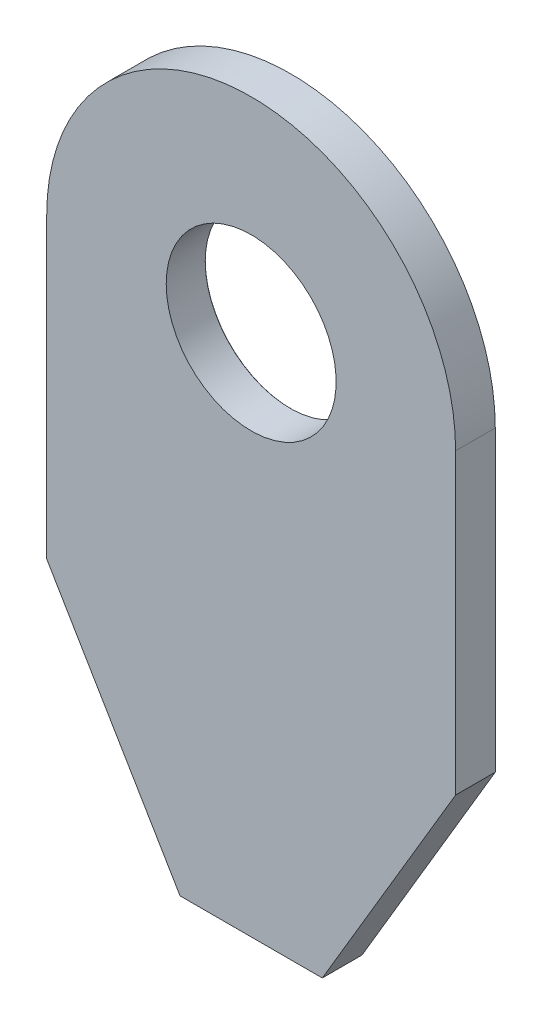
SolidWorks part; units mm, degrees
ref_plane "Front Plane" through (0, 0, 0) normal (0, 0, 1) x (1, 0, 0)
ref_plane "Top Plane" through (0, 0, 0) normal (0, 1, 0) x (1, 0, 0)
ref_plane "Right Plane" through (0, 0, 0) normal (1, 0, 0) x (0, 0, -1)
sketch "Sketch1" plane through (0, 0, 0) normal (0, 0, 1) x (1, 0, 0)
  line L0 (-7.94, 0) -> (-7.94, -11.5784)
  line L1 (-2.7621, -20.32) -> (2.7621, -20.32)
  line L2 (7.94, -11.5784) -> (7.94, 0)
  line L3 (7.94, -11.5784) -> (2.7621, -20.32)
  line L7 (7.94, -11.5784) -> (2.7621, -20.32)
  line L8 (-7.94, -11.5784) -> (-2.7621, -20.32)
  circle A0 centre (0, 0) radius 7.94
  dimension "D1" = 15.88
  dimension "D3" = 10.16
  dimension "D4" = 61.279
  dimension "D2" = 20.32
extrude "Boss-Extrude1" add sketch "Sketch1" along normal blind 1.54 contours A0 L0 L1 L2
hole_wizard "M6 Clearance Hole1" positions "Sketch4" profile "Sketch3" hole size "M6" standard "ANSI Metric" end condition through all
sketch "Sketch4" plane through (0, 0, 0) normal (0, 0, -1) x (-1, 0, 0)
  point P0 (0, 0)
sketch "Sketch3" plane through (0, 0, 0) normal (1, 0, 0) x (0, 1, 0)
  line L0 (0, 0) -> (0, 1.54)
  line L1 (0, 1.54) -> (3.3, 1.54)
  line L2 (3.3, 1.54) -> (3.3, 0.025)
  line L3 (3.3, 0.025) -> (3.325, 0)
  line L5 (3.325, 0) -> (0, 0)
  line L6 (-3.3, 0.025) -> (-3.325, 0) construction
  line L11 (0, -6.35) -> (0, 107.95) construction
  dimension "Thru Hole Dia." = 6.6
  dimension "Thru Hole Depth" = 1.54
  dimension "Near C'Sink Dia." = 6.65
  dimension "Near C'Sink Angle" = 90
